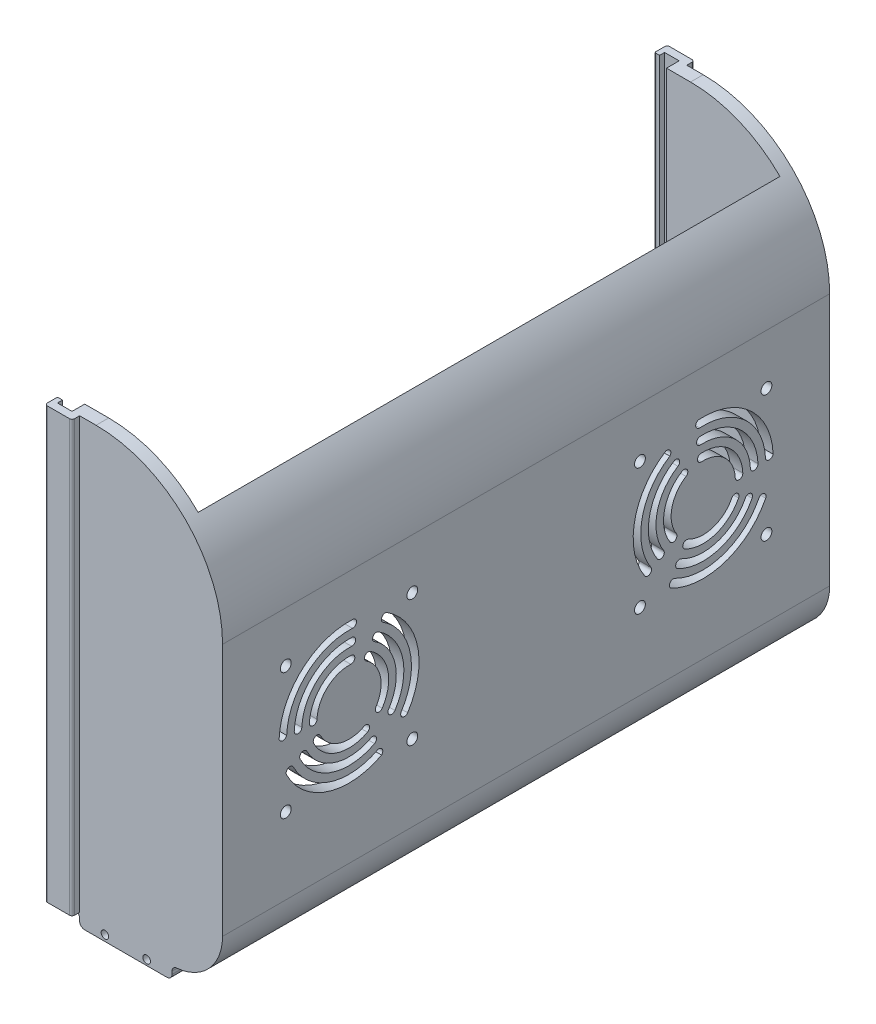
SolidWorks part; units mm, degrees
ref_plane "Plan de face" through (0, 0, 0) normal (0, 0, 1) x (1, 0, 0)
ref_plane "Plan de dessus" through (0, 0, 0) normal (0, 1, 0) x (1, 0, 0)
ref_plane "Plan de droite" through (0, 0, 0) normal (1, 0, 0) x (0, 0, -1)
sketch "Esquisse1" plane through (0, 0, 0) normal (0, 0, 1) x (1, 0, 0)
  line L0 (0, 8.8453) -> (10, 8.8453)
  line L1 (60, -41.1547) -> (60, -141.1547)
  line L2 (40, -161.1547) -> (0, -161.1547)
  line L3 (0, 8.8453) -> (0, -161.1547)
  arc A0 (10, 8.8453) -> (60, -41.1547) centre (10, -41.1547) cw
  arc A1 (60, -141.1547) -> (40, -161.1547) centre (40, -141.1547) cw
  point P11 (60, -161.1547)
  dimension "D2" = 50
  dimension "D3" = 20
  dimension "D1" = 60
extrude "Boss.-Extru.1" add sketch "Esquisse1" against normal blind 5
sketch "Esquisse2" plane through (0, 0, -5) normal (0, 0, -1) x (-1, 0, 0)
  line L0 (0, -156.1547) -> (0, -161.1547)
  line L1 (-60, -141.1547) -> (-60, -41.1547) construction
  line L2 (-60, -141.1547) -> (-60, -41.1547)
  line L3 (0, -161.1547) -> (-40, -161.1547) construction
  line L4 (-55, -141.1547) -> (-55, -41.1547)
  line L5 (0, -156.1547) -> (-40, -156.1547)
  line L6 (0, -156.1547) -> (-40, -156.1547)
  line L7 (0, -161.1547) -> (-40, -161.1547)
  line L8 (-45.3553, -5.7993) -> (-41.8198, -9.3349)
  arc A1 (-60, -141.1547) -> (-40, -161.1547) centre (-40, -141.1547) ccw construction
  arc A2 (-55, -141.1547) -> (-40, -156.1547) centre (-40, -141.1547) ccw
  arc A3 (-55, -141.1547) -> (-40, -156.1547) centre (-40, -141.1547) ccw
  arc A4 (-10, 3.8453) -> (-55, -41.1547) centre (-10, -41.1547) ccw
  arc A5 (-41.8198, -9.3349) -> (-55, -41.1547) centre (-10, -41.1547) ccw
  arc A6 (-10, 8.8453) -> (-60, -41.1547) centre (-10, -41.1547) ccw construction
  arc A7 (-60, -141.1547) -> (-40, -161.1547) centre (-40, -141.1547) ccw
  arc A8 (-45.3553, -5.7993) -> (-60, -41.1547) centre (-10, -41.1547) ccw
  dimension "D1" = 5
  dimension "D2" = 5
extrude "Boss.-Extru.3" add sketch "Esquisse2" along normal blind 230
sketch "Esquisse3" plane through (0, 0, -235) normal (0, 0, -1) x (-1, 0, 0)
  line L0 (-10, 8.8453) -> (0, 8.8453) construction
  line L1 (0, 8.8453) -> (0, -161.1547) construction
  line L2 (-40, -161.1547) -> (0, -161.1547) construction
  line L3 (-60, -41.1547) -> (-60, -141.1547) construction
  line L4 (-10, 8.8453) -> (0, 8.8453)
  line L5 (0, 8.8453) -> (0, -161.1547)
  line L6 (-40, -161.1547) -> (0, -161.1547)
  line L7 (-60, -41.1547) -> (-60, -141.1547)
  arc A0 (-60, -141.1547) -> (-40, -161.1547) centre (-40, -141.1547) ccw construction
  arc A1 (-10, 8.8453) -> (-45.3553, -5.7993) centre (-10, -41.1547) ccw construction
  arc A2 (-45.3553, -5.7993) -> (-60, -41.1547) centre (-10, -41.1547) ccw construction
  arc A3 (-60, -141.1547) -> (-40, -161.1547) centre (-40, -141.1547) ccw
  arc A4 (-10, 8.8453) -> (-45.3553, -5.7993) centre (-10, -41.1547) ccw
  arc A5 (-45.3553, -5.7993) -> (-60, -41.1547) centre (-10, -41.1547) ccw
extrude "Boss.-Extru.4" add sketch "Esquisse3" along normal up to surface (5 mm away)
sketch "Esquisse4" plane through (60, 0, 0) normal (1, 0, 0) x (0, 0, -1)
  circle A0 centre (215, -61) radius 2.15 construction
  circle A1 centre (215, -111) radius 2.15 construction
  circle A2 centre (165, -111) radius 2.15 construction
  circle A3 centre (165, -61) radius 2.15 construction
  circle A4 centre (215, -61) radius 2.15
  circle A5 centre (215, -111) radius 2.15
  circle A6 centre (165, -111) radius 2.15
  circle A7 centre (165, -61) radius 2.15
extrude "Enlèv. mat.-Extru.1" cut sketch "Esquisse4" against normal blind 5
sketch "Esquisse6" plane through (60, 0, 0) normal (1, 0, 0) x (0, 0, -1)
  circle A0 centre (190, -86) radius 17.2 construction
  circle A1 centre (190, -86) radius 17.2 construction
  arc A2 (202.6669, -85.4899) -> (189.296, -73.3424) centre (190, -86) ccw
  circle A3 centre (190, -86) radius 12.6771 construction
  arc A4 (205.6644, -85.3692) -> (189.1294, -70.3471) centre (190, -86) ccw
  arc A5 (189.1294, -70.3471) -> (189.296, -73.3424) centre (189.2127, -71.8448) ccw
  arc A6 (205.6644, -85.3692) -> (202.6669, -85.4899) centre (204.1656, -85.4295) cw
  arc A7 (203.9912, -93.0725) -> (201.3138, -91.7191) centre (202.6525, -92.3958) ccw
  arc A8 (184.1083, -97.2249) -> (201.3138, -91.7191) centre (190, -86) ccw
  arc A9 (182.7141, -99.8812) -> (184.1083, -97.2249) centre (183.4112, -98.553) cw
  arc A10 (182.7141, -99.8812) -> (203.9912, -93.0725) centre (190, -86) ccw
  arc A11 (176.8795, -94.5805) -> (179.3902, -92.9385) centre (178.1349, -93.7595) ccw
  arc A12 (183.2248, -75.2852) -> (179.3902, -92.9385) centre (190, -86) ccw
  arc A13 (181.6215, -72.7496) -> (183.2248, -75.2852) centre (182.4231, -74.0174) cw
  arc A14 (181.6215, -72.7496) -> (176.8795, -94.5805) centre (190, -86) ccw
  arc A15 (211.6596, -85.1277) -> (188.7961, -64.3563) centre (190, -86) ccw
  arc A16 (179.9256, -105.1939) -> (209.3459, -95.7793) centre (190, -86) ccw
  arc A17 (178.4148, -67.6784) -> (171.858, -97.8644) centre (190, -86) ccw
  arc A18 (180.0182, -70.214) -> (174.3687, -96.2224) centre (190, -86) ccw
  arc A19 (181.3199, -102.5375) -> (206.6685, -94.4259) centre (190, -86) ccw
  arc A20 (208.662, -85.2485) -> (188.9628, -67.3517) centre (190, -86) ccw
  arc A21 (178.4148, -67.6784) -> (180.0182, -70.214) centre (179.2165, -68.9462) cw
  arc A22 (188.7961, -64.3563) -> (188.9628, -67.3517) centre (188.8795, -65.854) ccw
  arc A23 (211.6596, -85.1277) -> (208.662, -85.2485) centre (210.1608, -85.1881) cw
  arc A24 (206.6685, -94.4259) -> (209.3459, -95.7793) centre (208.0072, -95.1026) cw
  arc A25 (181.3199, -102.5375) -> (179.9256, -105.1939) centre (180.6227, -103.8657) ccw
  arc A26 (174.3687, -96.2224) -> (171.858, -97.8644) centre (173.1133, -97.0434) cw
  arc A27 (180.0182, -70.214) -> (172.0212, -91.0595) centre (190, -86) ccw
  arc A28 (172.0212, -91.0595) -> (172.0212, -91.0595) centre (172.0212, -91.0595) cw
  arc A29 (217.6547, -84.8863) -> (188.4629, -58.3656) centre (190, -86) ccw
  arc A30 (214.6571, -85.007) -> (188.6295, -61.361) centre (190, -86) ccw
  arc A31 (188.6295, -61.361) -> (188.4629, -58.3656) centre (188.5462, -59.8633) cw
  arc A33 (214.6571, -85.007) -> (217.6547, -84.8863) centre (216.1387, -84.5179) ccw
  arc A34 (178.5314, -107.8502) -> (177.1371, -110.5065) centre (178.2142, -109.3778) ccw
  arc A35 (178.5314, -107.8502) -> (212.0233, -97.1327) centre (190, -86) ccw
  arc A36 (177.1371, -110.5065) -> (214.7006, -98.4861) centre (190, -86) ccw
  arc A37 (212.0233, -97.1327) -> (214.7006, -98.4861) centre (213.3619, -97.8094) cw
  arc A38 (176.8115, -65.1428) -> (175.2082, -62.6072) centre (175.6471, -64.1043) ccw
  arc A39 (176.8115, -65.1428) -> (169.3472, -99.5064) centre (190, -86) ccw
  arc A40 (175.2082, -62.6072) -> (166.8364, -101.1483) centre (190, -86) ccw
  arc A41 (169.3472, -99.5064) -> (166.8364, -101.1483) centre (168.0918, -100.3274) cw
  point P27 (190, -86)
  point P77 (190, -86)
  dimension "D3" = 3
  dimension "D2" = 6
  dimension "D1" = 3
  dimension "D4" = 6
  dimension "D5" = 3
extrude "Enlèv. mat.-Extru.2" cut sketch "Esquisse6" against normal blind 5 contours A41 A39 A38 A40 | A26 A18 A21 A17 | A13 A14 A11 A12 | A6 A4 A5 A2 | A23 A15 A22 A20 | A30 A33 A29 A31 | A9 A10 A7 A8 | A19 A25 A16 A24 | A37 A35 A34 A36
sketch "Esquisse7" plane through (60, 0, 0) normal (1, 0, 0) x (0, 0, -1)
  line L0 (120, -41.1547) -> (120, -141.1547) construction
  line L1 (240, -41.1547) -> (0, -41.1547) construction
  line L2 (240, -141.1547) -> (0, -141.1547) construction
  arc A0 (214.7006, -98.4861) -> (212.0233, -97.1327) centre (213.3619, -97.8094) ccw construction
  arc A1 (209.3459, -95.7793) -> (206.6685, -94.4259) centre (208.0072, -95.1026) ccw construction
  arc A2 (203.9912, -93.0725) -> (201.3138, -91.7191) centre (202.6525, -92.3958) ccw construction
  arc A3 (178.5314, -107.8502) -> (177.1371, -110.5065) centre (178.2142, -109.3778) ccw construction
  arc A4 (181.3199, -102.5375) -> (179.9256, -105.1939) centre (180.6227, -103.8657) ccw construction
  arc A5 (184.1083, -97.2249) -> (182.7141, -99.8812) centre (183.4112, -98.553) ccw construction
  arc A6 (184.1083, -97.2249) -> (201.3138, -91.7191) centre (190, -86) ccw construction
  arc A7 (182.7141, -99.8812) -> (203.9912, -93.0725) centre (190, -86) ccw construction
  arc A8 (181.3199, -102.5375) -> (206.6685, -94.4259) centre (190, -86) ccw construction
  arc A9 (179.9256, -105.1939) -> (209.3459, -95.7793) centre (190, -86) ccw construction
  arc A10 (178.5314, -107.8502) -> (212.0233, -97.1327) centre (190, -86) ccw construction
  arc A11 (177.1371, -110.5065) -> (214.7006, -98.4861) centre (190, -86) ccw construction
  circle A12 centre (165, -111) radius 2.15 construction
  circle A13 centre (215, -111) radius 2.15 construction
  circle A14 centre (215, -61) radius 2.15 construction
  circle A15 centre (165, -61) radius 2.15 construction
  arc A16 (214.7006, -98.4861) -> (212.0233, -97.1327) centre (213.3619, -97.8094) ccw construction
  arc A17 (209.3459, -95.7793) -> (206.6685, -94.4259) centre (208.0072, -95.1026) ccw construction
  arc A18 (203.9912, -93.0725) -> (201.3138, -91.7191) centre (202.6525, -92.3958) ccw construction
  arc A19 (178.5314, -107.8502) -> (177.1371, -110.5065) centre (178.2142, -109.3778) ccw construction
  arc A20 (181.3199, -102.5375) -> (179.9256, -105.1939) centre (180.6227, -103.8657) ccw construction
  arc A21 (184.1083, -97.2249) -> (182.7141, -99.8812) centre (183.4112, -98.553) ccw construction
  arc A22 (184.1083, -97.2249) -> (201.3138, -91.7191) centre (190, -86) ccw construction
  arc A23 (182.7141, -99.8812) -> (203.9912, -93.0725) centre (190, -86) ccw construction
  arc A24 (181.3199, -102.5375) -> (206.6685, -94.4259) centre (190, -86) ccw construction
  arc A25 (179.9256, -105.1939) -> (209.3459, -95.7793) centre (190, -86) ccw construction
  arc A26 (178.5314, -107.8502) -> (212.0233, -97.1327) centre (190, -86) ccw construction
  arc A27 (177.1371, -110.5065) -> (214.7006, -98.4861) centre (190, -86) ccw construction
  circle A28 centre (165, -111) radius 2.15 construction
  circle A29 centre (215, -111) radius 2.15 construction
  circle A30 centre (215, -61) radius 2.15 construction
  circle A31 centre (165, -61) radius 2.15 construction
  arc A32 (188.4629, -58.3656) -> (188.6295, -61.361) centre (188.5462, -59.8633) ccw construction
  arc A33 (188.7961, -64.3563) -> (188.9628, -67.3517) centre (188.8795, -65.854) ccw construction
  arc A34 (202.6669, -85.4899) -> (205.6644, -85.3692) centre (204.1656, -85.4295) ccw construction
  arc A35 (208.662, -85.2485) -> (211.6596, -85.1277) centre (210.1608, -85.1881) ccw construction
  arc A36 (214.6571, -85.007) -> (217.6547, -84.8863) centre (216.1387, -84.5179) ccw construction
  arc A37 (217.6547, -84.8863) -> (188.4629, -58.3656) centre (190, -86) ccw construction
  arc A38 (214.6571, -85.007) -> (188.6295, -61.361) centre (190, -86) ccw construction
  arc A39 (211.6596, -85.1277) -> (188.7961, -64.3563) centre (190, -86) ccw construction
  arc A40 (208.662, -85.2485) -> (188.9628, -67.3517) centre (190, -86) ccw construction
  arc A41 (205.6644, -85.3692) -> (189.1294, -70.3471) centre (190, -86) ccw construction
  arc A42 (202.6669, -85.4899) -> (189.296, -73.3424) centre (190, -86) ccw construction
  arc A43 (176.8795, -94.5805) -> (179.3902, -92.9385) centre (178.1349, -93.7595) ccw construction
  arc A44 (171.858, -97.8644) -> (174.3687, -96.2224) centre (173.1133, -97.0434) ccw construction
  arc A45 (166.8364, -101.1483) -> (169.3472, -99.5064) centre (168.0918, -100.3274) ccw construction
  arc A46 (176.8115, -65.1428) -> (175.2082, -62.6072) centre (175.6471, -64.1043) ccw construction
  arc A47 (180.0182, -70.214) -> (178.4148, -67.6784) centre (179.2165, -68.9462) ccw construction
  arc A48 (183.2248, -75.2852) -> (181.6215, -72.7496) centre (182.4231, -74.0174) ccw construction
  arc A49 (183.2248, -75.2852) -> (179.3902, -92.9385) centre (190, -86) ccw construction
  arc A50 (181.6215, -72.7496) -> (176.8795, -94.5805) centre (190, -86) ccw construction
  arc A51 (180.0182, -70.214) -> (174.3687, -96.2224) centre (190, -86) ccw construction
  arc A52 (178.4148, -67.6784) -> (171.858, -97.8644) centre (190, -86) ccw construction
  arc A53 (176.8115, -65.1428) -> (169.3472, -99.5064) centre (190, -86) ccw construction
  arc A54 (175.2082, -62.6072) -> (166.8364, -101.1483) centre (190, -86) ccw construction
  arc A55 (188.4629, -58.3656) -> (188.6295, -61.361) centre (188.5462, -59.8633) ccw construction
  arc A56 (188.7961, -64.3563) -> (188.9628, -67.3517) centre (188.8795, -65.854) ccw construction
  arc A57 (202.6669, -85.4899) -> (205.6644, -85.3692) centre (204.1656, -85.4295) ccw construction
  arc A58 (208.662, -85.2485) -> (211.6596, -85.1277) centre (210.1608, -85.1881) ccw construction
  arc A59 (214.6571, -85.007) -> (217.6547, -84.8863) centre (216.1387, -84.5179) ccw construction
  arc A60 (217.6547, -84.8863) -> (188.4629, -58.3656) centre (190, -86) ccw construction
  arc A61 (214.6571, -85.007) -> (188.6295, -61.361) centre (190, -86) ccw construction
  arc A62 (211.6596, -85.1277) -> (188.7961, -64.3563) centre (190, -86) ccw construction
  arc A63 (208.662, -85.2485) -> (188.9628, -67.3517) centre (190, -86) ccw construction
  arc A64 (205.6644, -85.3692) -> (189.1294, -70.3471) centre (190, -86) ccw construction
  arc A65 (202.6669, -85.4899) -> (189.296, -73.3424) centre (190, -86) ccw construction
  arc A66 (176.8795, -94.5805) -> (179.3902, -92.9385) centre (178.1349, -93.7595) ccw construction
  arc A67 (171.858, -97.8644) -> (174.3687, -96.2224) centre (173.1133, -97.0434) ccw construction
  arc A68 (166.8364, -101.1483) -> (169.3472, -99.5064) centre (168.0918, -100.3274) ccw construction
  arc A69 (176.8115, -65.1428) -> (175.2082, -62.6072) centre (175.6471, -64.1043) ccw construction
  arc A70 (180.0182, -70.214) -> (178.4148, -67.6784) centre (179.2165, -68.9462) ccw construction
  arc A71 (183.2248, -75.2852) -> (181.6215, -72.7496) centre (182.4231, -74.0174) ccw construction
  arc A72 (183.2248, -75.2852) -> (179.3902, -92.9385) centre (190, -86) ccw construction
  arc A73 (181.6215, -72.7496) -> (176.8795, -94.5805) centre (190, -86) ccw construction
  arc A74 (180.0182, -70.214) -> (174.3687, -96.2224) centre (190, -86) ccw construction
  arc A75 (178.4148, -67.6784) -> (171.858, -97.8644) centre (190, -86) ccw construction
  arc A76 (176.8115, -65.1428) -> (169.3472, -99.5064) centre (190, -86) ccw construction
  arc A77 (175.2082, -62.6072) -> (166.8364, -101.1483) centre (190, -86) ccw construction
  arc A78 (189.1294, -70.3471) -> (189.296, -73.3424) centre (189.2127, -71.8448) ccw construction
  arc A79 (189.1294, -70.3471) -> (189.296, -73.3424) centre (189.2127, -71.8448) ccw construction
  arc A80 (50.8706, -70.3471) -> (50.704, -73.3424) centre (50.7873, -71.8448) cw
  arc A81 (64.7918, -62.6072) -> (73.1636, -101.1483) centre (50, -86) cw
  arc A82 (63.1885, -65.1428) -> (70.6528, -99.5064) centre (50, -86) cw
  arc A83 (61.5852, -67.6784) -> (68.142, -97.8644) centre (50, -86) cw
  arc A84 (59.9818, -70.214) -> (65.6313, -96.2224) centre (50, -86) cw
  arc A85 (58.3785, -72.7496) -> (63.1205, -94.5805) centre (50, -86) cw
  arc A86 (56.7752, -75.2852) -> (60.6098, -92.9385) centre (50, -86) cw
  arc A87 (56.7752, -75.2852) -> (58.3785, -72.7496) centre (57.5769, -74.0174) cw
  arc A88 (59.9818, -70.214) -> (61.5852, -67.6784) centre (60.7835, -68.9462) cw
  arc A89 (63.1885, -65.1428) -> (64.7918, -62.6072) centre (64.3529, -64.1043) cw
  arc A90 (73.1636, -101.1483) -> (70.6528, -99.5064) centre (71.9082, -100.3274) cw
  arc A91 (68.142, -97.8644) -> (65.6313, -96.2224) centre (66.8867, -97.0434) cw
  arc A92 (63.1205, -94.5805) -> (60.6098, -92.9385) centre (61.8651, -93.7595) cw
  arc A93 (37.3331, -85.4899) -> (50.704, -73.3424) centre (50, -86) cw
  arc A94 (34.3356, -85.3692) -> (50.8706, -70.3471) centre (50, -86) cw
  arc A95 (31.338, -85.2485) -> (51.0372, -67.3517) centre (50, -86) cw
  arc A96 (28.3404, -85.1277) -> (51.2039, -64.3563) centre (50, -86) cw
  arc A97 (25.3429, -85.007) -> (51.3705, -61.361) centre (50, -86) cw
  arc A98 (22.3453, -84.8863) -> (51.5371, -58.3656) centre (50, -86) cw
  arc A99 (25.3429, -85.007) -> (22.3453, -84.8863) centre (23.8613, -84.5179) cw
  arc A100 (31.338, -85.2485) -> (28.3404, -85.1277) centre (29.8392, -85.1881) cw
  arc A101 (37.3331, -85.4899) -> (34.3356, -85.3692) centre (35.8344, -85.4295) cw
  arc A102 (51.2039, -64.3563) -> (51.0372, -67.3517) centre (51.1205, -65.854) cw
  arc A103 (51.5371, -58.3656) -> (51.3705, -61.361) centre (51.4538, -59.8633) cw
  circle A104 centre (75, -61) radius 2.15
  circle A105 centre (25, -61) radius 2.15
  circle A106 centre (25, -111) radius 2.15
  circle A107 centre (75, -111) radius 2.15
  arc A108 (62.8629, -110.5065) -> (25.2994, -98.4861) centre (50, -86) cw
  arc A109 (61.4686, -107.8502) -> (27.9767, -97.1327) centre (50, -86) cw
  arc A110 (60.0744, -105.1939) -> (30.6541, -95.7793) centre (50, -86) cw
  arc A111 (58.6801, -102.5375) -> (33.3315, -94.4259) centre (50, -86) cw
  arc A112 (57.2859, -99.8812) -> (36.0088, -93.0725) centre (50, -86) cw
  arc A113 (55.8917, -97.2249) -> (38.6862, -91.7191) centre (50, -86) cw
  arc A114 (55.8917, -97.2249) -> (57.2859, -99.8812) centre (56.5888, -98.553) cw
  arc A115 (58.6801, -102.5375) -> (60.0744, -105.1939) centre (59.3773, -103.8657) cw
  arc A116 (61.4686, -107.8502) -> (62.8629, -110.5065) centre (61.7858, -109.3778) cw
  arc A117 (36.0088, -93.0725) -> (38.6862, -91.7191) centre (37.3475, -92.3958) cw
  arc A118 (30.6541, -95.7793) -> (33.3315, -94.4259) centre (31.9928, -95.1026) cw
  arc A119 (25.2994, -98.4861) -> (27.9767, -97.1327) centre (26.6381, -97.8094) cw
extrude "Enlèv. mat.-Extru.3" cut sketch "Esquisse7" against normal blind 5
sketch "Esquisse8" plane through (0, -161.1547, 0) normal (0, -1, 0) x (1, 0, 0)
  line L0 (0, -240) -> (40, -240) construction
  circle A0 centre (20, -200) radius 10
  circle A1 centre (20, -170) radius 10
  circle A2 centre (20, -140) radius 10
  point P6 (20, -240)
  dimension "D3" = 20
  dimension "D4" = 20
  dimension "D5" = 20
  dimension "D6" = 30
  dimension "D1" = 30
  dimension "D2" = 40
extrude "Enlèv. mat.-Extru.4" cut sketch "Esquisse8" against normal blind 5
sketch "Esquisse9" plane through (0, 8.8453, 0) normal (0, 1, 0) x (1, 0, 0)
  line L0 (10, 240) -> (0, 240) construction
  line L1 (0, 235) -> (1, 235)
  line L2 (0, 235) -> (0, 240)
  line L3 (0, 240) -> (1, 240)
  line L4 (1, 235) -> (1, 240)
  line L5 (10, 5) -> (0, 5) construction
  line L6 (0, 0) -> (1, 0)
  line L7 (0, 0) -> (0, 5)
  line L8 (0, 5) -> (1, 5)
  line L9 (1, 0) -> (1, 5)
  dimension "D1" = 1
  dimension "D2" = 1
extrude "Enlèv. mat.-Extru.5" cut sketch "Esquisse9" against normal blind 231
sketch "Esquisse10" plane through (0, 8.8453, 0) normal (0, 1, 0) x (1, 0, 0)
  line L1 (2.5, 243) -> (-6.25, 243)
  line L2 (-7.25, 242) -> (-7.25, 238.5)
  line L3 (-6.75, 238) -> (-5.25, 238)
  line L5 (-5.25, 238) -> (-5.25, 240)
  line L6 (-5.25, 240) -> (0.5, 240)
  line L7 (0.5, 240) -> (0.5, 235)
  line L8 (0.5, 235) -> (3.5, 235)
  line L11 (3.5, 242) -> (3.5, 235)
  line L12 (0, 0) -> (0, 240) construction
  line L13 (-5, 0) -> (-5, 240) construction
  line L14 (-5, 240) -> (0, 240) construction
  line L15 (1, 235) -> (10, 235) construction
  line L16 (0.5, 5) -> (3.5, 5)
  line L17 (10, 5) -> (1, 5) construction
  line L18 (3.5, 5) -> (3.5, -2)
  line L19 (2.5, -3) -> (-6.25, -3)
  line L20 (-7.25, -2) -> (-7.25, 1.5)
  line L21 (-6.75, 2) -> (-5.25, 2)
  line L22 (-5.25, 2) -> (-5.25, 0)
  line L23 (-5.25, 0) -> (0.5, 0)
  line L24 (0.5, 0) -> (0.5, 5)
  line L25 (-5, 0) -> (0, 0) construction
  arc A0 (3.5, 242) -> (2.5, 243) centre (2.5, 242) ccw
  arc A1 (-6.25, 243) -> (-7.25, 242) centre (-6.25, 242) ccw
  arc A2 (-7.25, 238.5) -> (-6.75, 238) centre (-6.75, 238.5) ccw
  arc A3 (-6.25, -3) -> (-7.25, -2) centre (-6.25, -2) cw
  arc A4 (3.5, -2) -> (2.5, -3) centre (2.5, -2) cw
  arc A5 (-7.25, 1.5) -> (-6.75, 2) centre (-6.75, 1.5) cw
  point P4 (-5.25, 239)
  point P22 (-7.25, 243)
  point P25 (-7.25, 238)
  point P48 (-7.25, 2)
  dimension "D7" = 1
  dimension "D8" = 0.5
  dimension "D16" = 1
  dimension "D17" = 0.5
  dimension "D1" = 2
  dimension "D2" = 3
  dimension "D3" = 3
  dimension "D4" = 0.5
  dimension "D5" = 0.25
  dimension "D6" = 5
  dimension "D9" = 3
  dimension "D10" = 3
  dimension "D11" = 0.25
  dimension "D12" = 5
  dimension "D13" = 2
  dimension "D14" = 3
  dimension "D15" = 0.5
extrude "Boss.-Extru.5" add sketch "Esquisse10" against normal up to surface (170 mm away)
sketch "Esquisse11" plane through (0, -161.1547, 0) normal (0, -1, 0) x (1, 0, 0)
  line L0 (40, -240) -> (40, 0) construction
  line L1 (0, -235) -> (40, -235)
  line L2 (0, -235) -> (0, -5)
  line L3 (0, -5) -> (40, -5)
  line L4 (40, -235) -> (40, -5)
  line L5 (0, -5) -> (0.5, -5) construction
extrude "Enlèv. mat.-Extru.6" cut sketch "Esquisse11" against normal blind 5
sketch "Esquisse12" plane through (0, -161.1547, 0) normal (0, -1, 0) x (1, 0, 0)
  line L0 (3.5, 0) -> (3.5, -5)
  line L1 (3.5, -240) -> (3.5, -235)
  line L10 (0.5, -5) -> (40, -5)
  line L11 (40, -5) -> (40, 0)
  line L12 (40, 0) -> (3.5, 0)
  line L13 (3.5, 0) -> (3.5, 2)
  line L14 (2.5, 3) -> (-6.25, 3)
  line L15 (-7.25, 2) -> (-7.25, -1.5)
  line L16 (-6.75, -2) -> (-5.25, -2)
  line L17 (-5.25, -2) -> (-5.25, 0)
  line L18 (-5.25, 0) -> (0.5, 0)
  line L19 (0.5, 0) -> (0.5, -5)
  line L20 (3.5, -5) -> (40, -5)
  line L21 (40, -5) -> (40, 0)
  line L22 (40, 0) -> (3.5, 0)
  line L30 (40, -235) -> (0.5, -235)
  line L31 (0.5, -235) -> (0.5, -240)
  line L32 (0.5, -240) -> (-5.25, -240)
  line L33 (-5.25, -240) -> (-5.25, -238)
  line L34 (-5.25, -238) -> (-6.75, -238)
  line L35 (-7.25, -238.5) -> (-7.25, -242)
  line L36 (-6.25, -243) -> (2.5, -243)
  line L37 (3.5, -242) -> (3.5, -240)
  line L38 (3.5, -240) -> (40, -240)
  line L39 (40, -240) -> (40, -235)
  line L40 (40, -235) -> (3.5, -235)
  line L48 (3.5, -240) -> (40, -240)
  line L49 (40, -240) -> (40, -235)
  arc A3 (3.5, 2) -> (2.5, 3) centre (2.5, 2) ccw
  arc A4 (-6.25, 3) -> (-7.25, 2) centre (-6.25, 2) ccw
  arc A5 (-7.25, -1.5) -> (-6.75, -2) centre (-6.75, -1.5) ccw
  arc A9 (-6.75, -238) -> (-7.25, -238.5) centre (-6.75, -238.5) ccw
  arc A10 (-7.25, -242) -> (-6.25, -243) centre (-6.25, -242) ccw
  arc A11 (2.5, -243) -> (3.5, -242) centre (2.5, -242) ccw
  dimension "D1" = 0
  dimension "D2" = 0
extrude "Boss.-Extru.6" add sketch "Esquisse12" along normal blind 5
fillet "Congé1" radius 2 8 edges at (3.5, -161.1547, -2.5) (3.5, -166.1547, -2.5) (40, -166.1547, -2.5) (40, -161.1547, -2.5) (40, -166.1547, -237.5) (3.5, -161.1547, -237.5) (3.5, -166.1547, -237.5) (40, -161.1547, -237.5)
sketch "Esquisse13" plane through (0, 0, -240) normal (0, 0, -1) x (-1, 0, 0)
  line L0 (-3.5, -163.6547) -> (-40, -164.1547) construction
  line L1 (-3.5, -164.1547) -> (-3.5, -163.1547) construction
  circle A0 centre (-13.4991, -163.7917) radius 1.5
  circle A1 centre (-30, -164.0177) radius 1.5
  dimension "D1" = 3
  dimension "D2" = 3
  dimension "D3" = 10
  dimension "D4" = 10
extrude "Enlèv. mat.-Extru.7" cut sketch "Esquisse13" against normal blind 294
